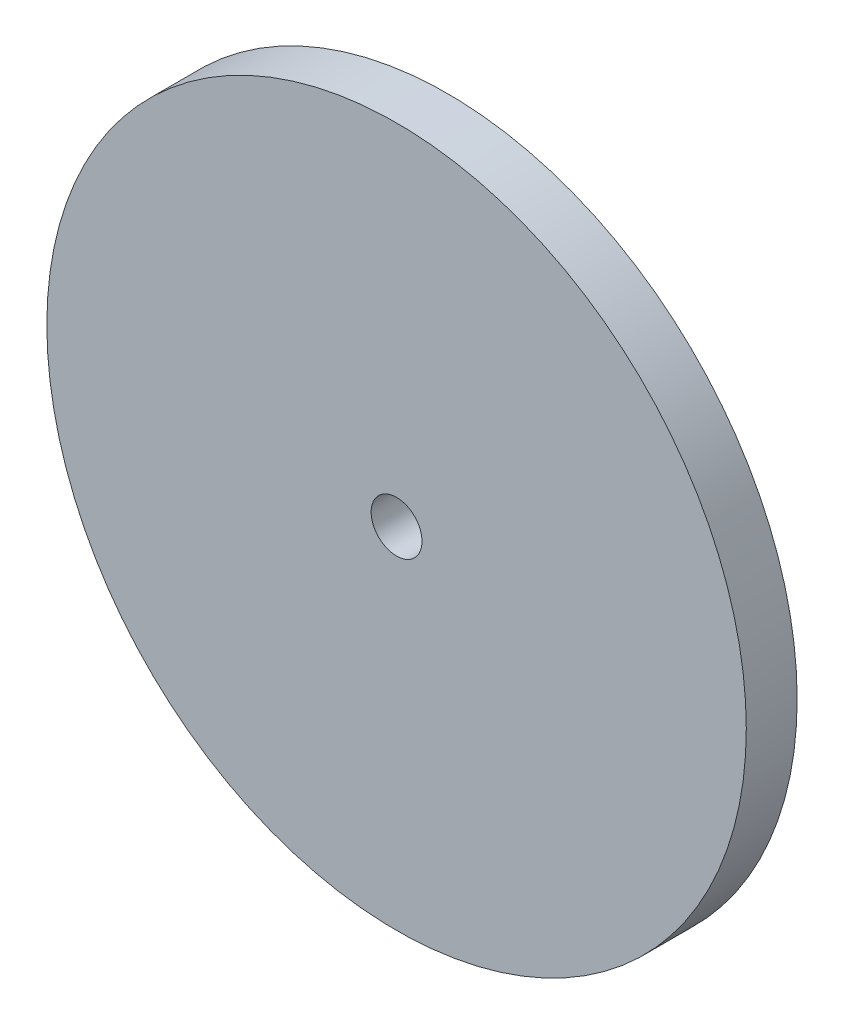
SolidWorks part; units mm, degrees
ref_plane "Plan de face" through (0, 0, 0) normal (0, 0, 1) x (1, 0, 0)
ref_plane "Plan de dessus" through (0, 0, 0) normal (0, 1, 0) x (1, 0, 0)
ref_plane "Plan de droite" through (0, 0, 0) normal (1, 0, 0) x (0, 0, -1)
sketch "Esquisse1" plane through (0, 0, 0) normal (0, 0, 1) x (1, 0, 0)
  circle A0 centre (0, 0) radius 27.5
  dimension "D1" = 55
extrude "Boss.-Extru.1" add sketch "Esquisse1" along normal blind 4
ref_plane "Plan1" through (0, 0, 2) normal (0, 0, 1) x (1, 0, 0)
sketch "Esquisse2" plane through (0, 0, 2) normal (0, 0, 1) x (1, 0, 0)
  circle A0 centre (0, 0) radius 2
  dimension "D1" = 4
extrude "Enlèv. mat.-Extru.1" cut sketch "Esquisse2" against normal mid plane 4
